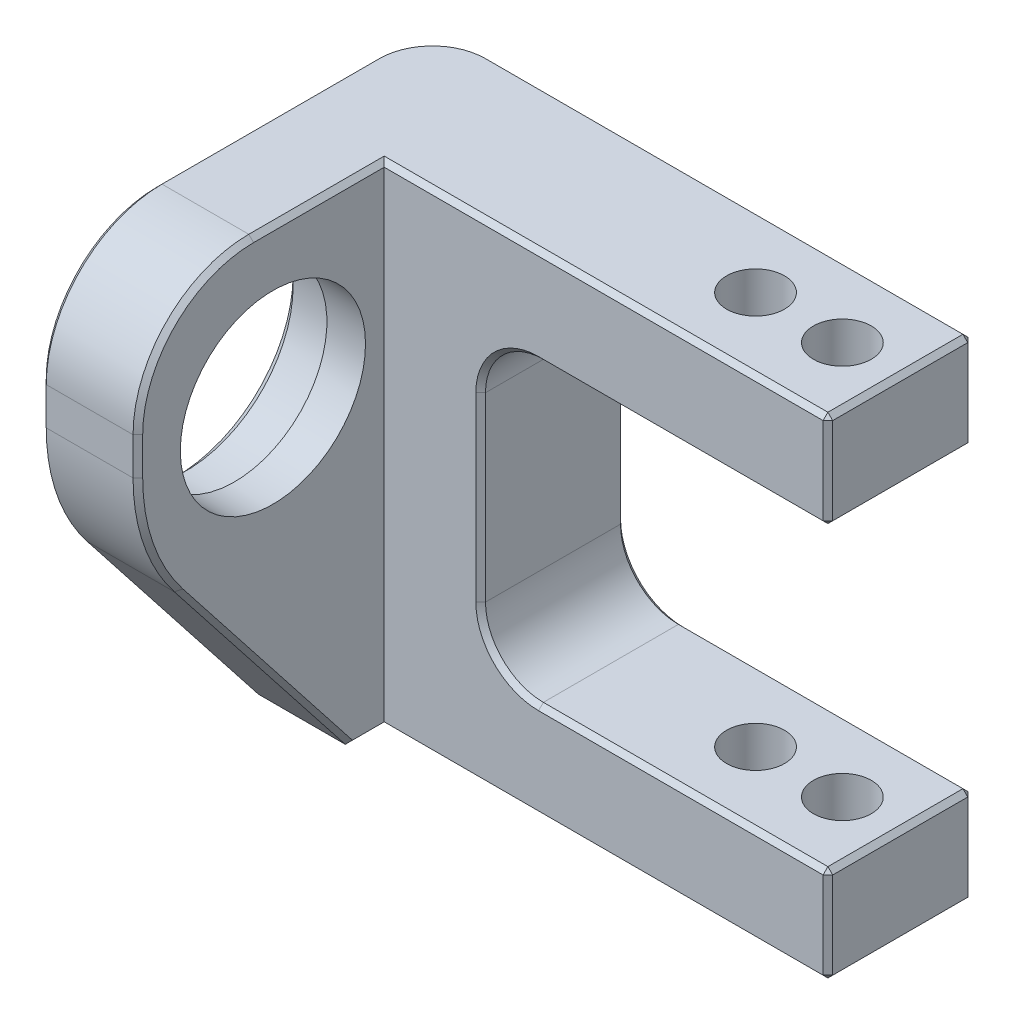
SolidWorks part; units mm, degrees
ref_plane "Front Plane" through (0, 0, 0) normal (0, 0, 1) x (1, 0, 0)
ref_plane "Top Plane" through (0, 0, 0) normal (0, 1, 0) x (1, 0, 0)
ref_plane "Right Plane" through (0, 0, 0) normal (1, 0, 0) x (0, 0, -1)
sketch "Sketch1" plane through (0, 0, 0) normal (0, 1, 0) x (1, 0, 0)
  line L0 (-56, 7.5) -> (-56, -33.04)
  line L1 (0, -7.5) -> (-46, -7.5)
  line L2 (0, -7.5) -> (0, 7.5)
  line L3 (0, 7.5) -> (-56, 7.5)
  line L7 (-56, -33.04) -> (-46, -33.04)
  line L8 (-46, -7.5) -> (-46, -33.04)
  point P3 (0, 0)
  dimension "D1" = 15
  dimension "D2" = 56
  dimension "D3" = 25.54
  dimension "D4" = 10
extrude "Boss-Extrude1" add sketch "Sketch1" along normal blind 50.8 contours L1 L8 L7 L0 L3 L2
sketch "Sketch2" plane through (-56, 0, 0) normal (-1, 0, 0) x (0, 0, 1)
  line L0 (7.5, 50.8) -> (7.5, 0) construction
  line L1 (7.5, 50.8) -> (7.5, 0) construction
  line L2 (-7.5, 50.8) -> (33.04, 50.8) construction
  circle A0 centre (19.04, 35.4) radius 11.1
  dimension "D2" = 22.2
  dimension "D1" = 15.4
  dimension "D3" = 11.54
extrude "Cut-Extrude1" cut sketch "Sketch2" against normal blind 6
sketch "Sketch4" plane through (-50, 0, 0) normal (-1, 0, 0) x (0, 0, 1)
  circle A2 centre (19.04, 35.4) radius 9.6
  circle A3 centre (19.04, 35.4) radius 9.6
  dimension "D1" = 1.5
extrude "Cut-Extrude2" cut sketch "Sketch4" against normal through all
sketch "Sketch5" plane through (0, 50.8, 0) normal (0, 1, 0) x (1, 0, 0)
  line L0 (0, -7.5) -> (0, 7.5) construction
  circle A0 centre (-6, 0) radius 3
  circle A1 centre (-15, 0) radius 3
  dimension "D1" = 6
  dimension "D2" = 6
  dimension "D3" = 9
extrude "Cut-Extrude3" cut sketch "Sketch5" against normal through all
sketch "Sketch6" plane through (-56, 0, 0) normal (-1, 0, 0) x (0, 0, 1)
  line L0 (7.5, 0) -> (33.04, 0) construction
  line L1 (11.04, 0) -> (33.04, 0)
  line L2 (11.04, 0) -> (33.04, 28)
  line L3 (33.04, 50.8) -> (33.04, 0) construction
  line L4 (33.04, 28) -> (33.04, 0)
  line L5 (-7.5, 0) -> (33.04, 0) construction
  dimension "D1" = 28
  dimension "D2" = 22
extrude "Cut-Extrude4" cut sketch "Sketch6" against normal through all
fillet "Fillet3" radius 20 1 edges at (-51, 28, 33.04)
fillet "Fillet4" radius 12 1 edges at (-51, 50.8, 33.04)
sketch "Sketch8" plane through (0, 0, 7.5) normal (0, 0, 1) x (1, 0, 0)
  line L0 (0, 50.8) -> (0, 0) construction
  line L1 (0, 40.8) -> (-36, 40.8)
  line L2 (0, 40.8) -> (0, 10)
  line L3 (0, 10) -> (-36, 10)
  line L4 (-36, 40.8) -> (-36, 10)
  line L5 (0, 50.8) -> (-46, 50.8) construction
  line L6 (0, 0) -> (-46, 0) construction
  line L7 (-46, 50.8) -> (-46, 0) construction
  dimension "D1" = 10
  dimension "D2" = 10
  dimension "D3" = 10
extrude "Cut-Extrude5" cut sketch "Sketch8" against normal through all
chamfer "Chamfer2" distance 1 angle 45 1 edges at (-56, 35.4, 30.14)
fillet "Fillet6" radius 6 1 edges at (-56, 25.4, -7.5)
fillet "Fillet5" radius 6 2 edges at (-36, 10, 0) (-36, 40.8, 0)
chamfer "Chamfer3" distance 0.5 angle 45 36 edges at (-15, 40.8, -7.5) (-25, 50.8, -7.5) (-36, 25.4, -7.5) (-15, 10, -7.5) (0, 0, 0) (-46, 0, 9.27) (-23, 0, 7.5) (0, 5, 7.5) (0, 50.8, 0) (0, 45.8, -7.5) (0, 40.8, 0) (-23, 50.8, 7.5) (0, 45.8, 7.5) (-15, 40.8, 7.5) (-36, 25.4, 7.5) (-15, 10, 7.5) (0, 10, 0) (0, 5, -7.5) (-25, 0, -7.5) (-56, 0, 4.77) (-56, 11.2804, 19.9032) (-56, 28.38, 31.9414) (-56, 36.8586, 33.04) (-56, 50.8, 9.77) (-56, 47.2853, 29.5253) (-46, 11.2804, 19.9032) (-46, 28.38, 31.9414) (-46, 50.8, 14.27) (-46, 36.8586, 33.04) (-46, 47.2853, 29.5253) (-34.2426, 39.0426, 7.5) (-34.2426, 11.7574, 7.5) (-34.2426, 39.0426, -7.5) (-34.2426, 11.7574, -7.5) (-54.2426, 0, -5.7426) (-54.2426, 50.8, -5.7426)
mirror "Mirror1" [suppressed]
delete or keep bodies "Body-Delete/Keep 1" [suppressed] type delete bodies bodies 107
